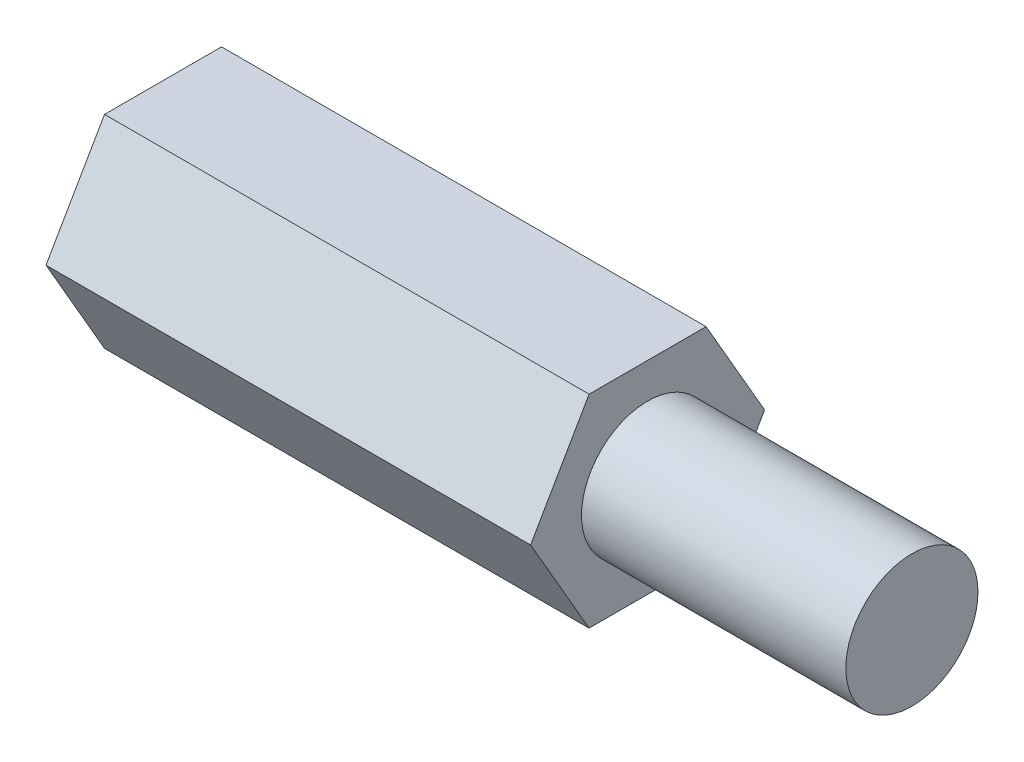
SolidWorks part; units mm, degrees
ref_plane "前视基准面" through (0, 0, 0) normal (0, 0, 1) x (1, 0, 0)
ref_plane "上视基准面" through (0, 0, 0) normal (0, 1, 0) x (1, 0, 0)
ref_plane "右视基准面" through (0, 0, 0) normal (1, 0, 0) x (0, 0, -1)
other "Configuration Table"
sketch "Sketch1" plane through (0, 0, 0) normal (1, 0, 0) x (0, 0, -1)
  line L1 (1.3279, 2.3) -> (-1.3279, 2.3)
  line L2 (-1.3279, 2.3) -> (-2.6558, 0)
  line L3 (-2.6558, 0) -> (-1.3279, -2.3)
  line L4 (-1.3279, -2.3) -> (1.3279, -2.3)
  line L5 (1.3279, -2.3) -> (2.6558, 0)
  line L6 (2.6558, 0) -> (1.3279, 2.3)
  circle A0 centre (0, 0) radius 1.5
  circle A1 centre (0, 0) radius 2.3 construction
  dimension "D1" = 4.6
  dimension "D2" = 3
extrude "Boss-Extrude1" add sketch "Sketch1" along normal blind 11
sketch "Sketch2" plane through (11, 0, 0) normal (1, 0, 0) x (0, 0, -1)
  circle A0 centre (0, 0) radius 1.5
  dimension "D1" = 3
extrude "Boss-Extrude2" add sketch "Sketch2" along normal blind 6 separate body
sketch "Sketch3" plane through (11, 0, 0) normal (-1, 0, 0) x (0, 0, 1)
  line L6 (-1.3279, 2.3) -> (-2.6558, 0)
  line L7 (-2.6558, 0) -> (-1.3279, -2.3)
  line L8 (-1.3279, -2.3) -> (1.3279, -2.3)
  line L9 (1.3279, -2.3) -> (2.6558, 0)
  line L10 (2.6558, 0) -> (1.3279, 2.3)
  line L11 (1.3279, 2.3) -> (-1.3279, 2.3)
  line L12 (-1.3279, 2.3) -> (-2.6558, 0)
  line L13 (-2.6558, 0) -> (-1.3279, -2.3)
  line L14 (-1.3279, -2.3) -> (1.3279, -2.3)
  line L15 (1.3279, -2.3) -> (2.6558, 0)
  line L16 (2.6558, 0) -> (1.3279, 2.3)
  line L17 (1.3279, 2.3) -> (-1.3279, 2.3)
  dimension "D1" = 0
extrude "Boss-Extrude3" add sketch "Sketch3" along normal blind 2
